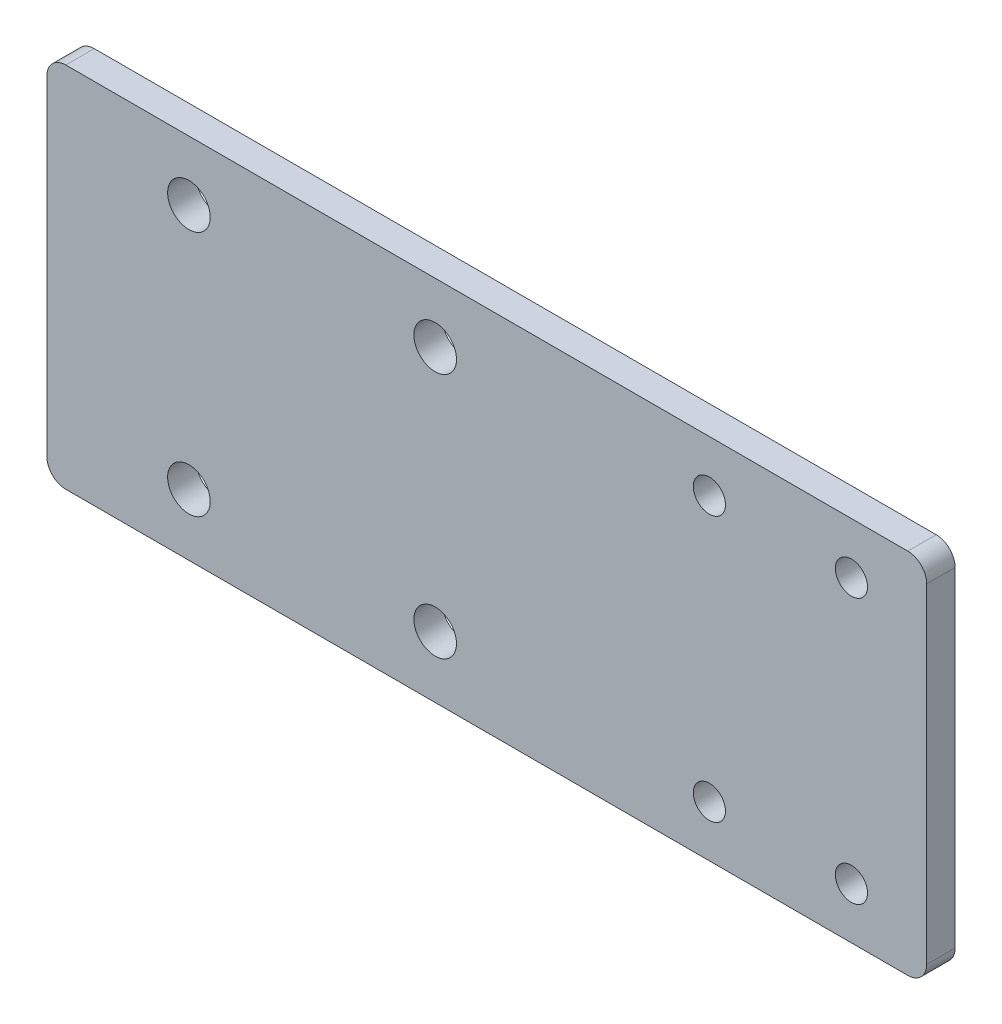
SolidWorks part; units mm, degrees
ref_plane "Front Plane" through (0, 0, 0) normal (0, 0, 1) x (1, 0, 0)
ref_plane "Top Plane" through (0, 0, 0) normal (0, 1, 0) x (1, 0, 0)
ref_plane "Right Plane" through (0, 0, 0) normal (1, 0, 0) x (0, 0, -1)
sketch "Model" plane through (0, 0, 0) normal (0, 0, 1) x (1, 0, 0)
  line L0 (-75.45, -19.4) -> (13.45, -19.4)
  line L1 (15.45, -17.4) -> (15.45, 17.4)
  line L2 (13.45, 19.4) -> (-75.45, 19.4)
  line L3 (-77.45, 17.4) -> (-77.45, -17.4)
  circle A0 centre (-62.45, 13.1) radius 2.25
  circle A1 centre (-36.45, 13.1) radius 2.25
  circle A2 centre (-36.45, -12.9) radius 2.25
  circle A3 centre (-62.45, -12.9) radius 2.25
  circle A4 centre (7.5, 14) radius 1.7
  circle A5 centre (-7.5, 14) radius 1.7
  circle A6 centre (-7.5, -14) radius 1.7
  circle A7 centre (7.5, -14) radius 1.7
  arc A8 (-77.45, -17.4) -> (-75.45, -19.4) centre (-75.45, -17.4) ccw
  arc A9 (13.45, -19.4) -> (15.45, -17.4) centre (13.45, -17.4) ccw
  arc A10 (15.45, 17.4) -> (13.45, 19.4) centre (13.45, 17.4) ccw
  arc A11 (-75.45, 19.4) -> (-77.45, 17.4) centre (-75.45, 17.4) ccw
extrude "Boss-Extrude1" add sketch "Model" along normal blind 3
